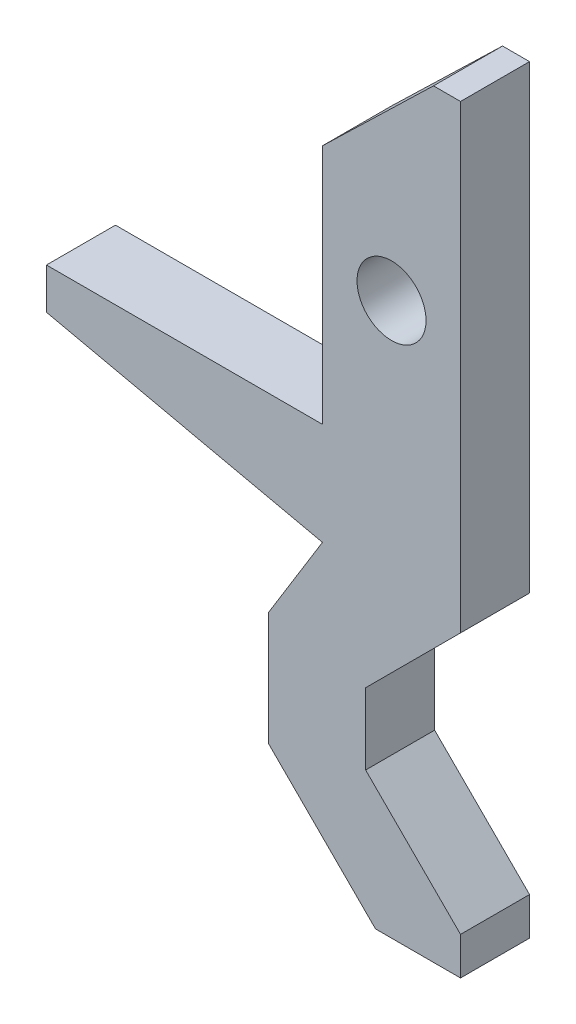
SolidWorks part; units mm, degrees
ref_plane "정면" through (0, 0, 0) normal (0, 0, 1) x (1, 0, 0)
ref_plane "윗면" through (0, 0, 0) normal (0, 1, 0) x (1, 0, 0)
ref_plane "우측면" through (0, 0, 0) normal (1, 0, 0) x (0, 0, -1)
sketch "스케치1" plane through (0, 0, 0) normal (0, 0, 1) x (1, 0, 0)
  line L0 (5, 0) -> (5, -18.3482)
  line L1 (5, -18.3482) -> (-1.8754, -25.2236)
  line L2 (-1.8754, -25.2236) -> (-1.8754, -30.3877)
  line L3 (-1.8754, -30.3877) -> (5, -37.2631)
  line L4 (5, -37.2631) -> (5, -40)
  line L5 (5, -40) -> (-1.1602, -40)
  line L6 (-1.1602, -40) -> (-8.9183, -32.242)
  line L7 (-8.9183, -32.242) -> (-8.9183, -24.0276)
  line L8 (-8.9183, -24.0276) -> (-5.0033, -17.6672)
  line L9 (-4.9997, -10.2618) -> (-5, 0)
  line L10 (-5, 0) -> (-5, 7.2202)
  line L11 (-5, 7.2202) -> (3.0425, 15)
  line L12 (3.0425, 15) -> (5, 15)
  line L13 (5, 15) -> (5, 0)
  line L14 (-5.0033, -17.6672) -> (-25, -13.2319)
  line L15 (-25, -13.2319) -> (-25, -10.2618)
  line L16 (-25, -10.2618) -> (-4.9997, -10.2618)
  circle A0 centre (0, 0) radius 2.5
  circle A1 centre (0, 0) radius 5
  point P23 (9.0187, -3.8874)
  point P24 (0.7406, 1.1296)
  dimension "D1" = 5
  dimension "D2" = 10
  dimension "D3" = 30
  dimension "D4" = 40
  dimension "D5" = 15
extrude "보스-돌출1" add sketch "스케치1" along normal blind 5 contours A1 L13 L12 L11 L10 | A1 A0 | A1 L9 L16 L15 L14 L8 L7 L6 L5 L4 L3 L2 L1 L0
